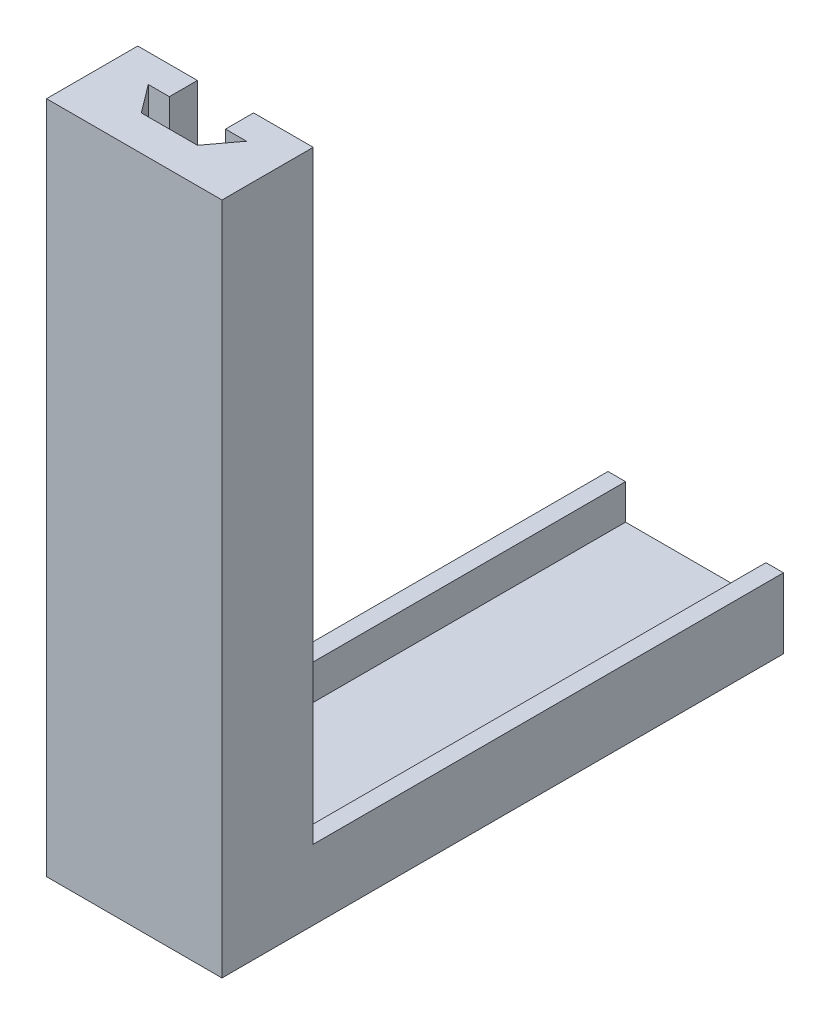
SolidWorks part; units mm, degrees
ref_plane "Front Plane" through (0, 0, 0) normal (0, 0, 1) x (1, 0, 0)
ref_plane "Top Plane" through (0, 0, 0) normal (0, 1, 0) x (1, 0, 0)
ref_plane "Right Plane" through (0, 0, 0) normal (1, 0, 0) x (0, 0, -1)
sketch "Sketch1" plane through (0, 0, 0) normal (0, 1, 0) x (1, 0, 0)
  line L1 (-12.5, -40) -> (12.5, -40)
  line L2 (-12.5, -40) -> (-12.5, 40)
  line L3 (-12.5, 40) -> (12.5, 40)
  line L4 (12.5, -40) -> (12.5, 40)
  line L5 (-12.5, -40) -> (12.5, 40) construction
  line L6 (-12.5, 40) -> (12.5, -40) construction
  point P0 (0, 0)
  dimension "D1" = 80
  dimension "D2" = 25
extrude "Boss-Extrude1" add sketch "Sketch1" along normal blind 10
sketch "Sketch2" plane through (0, 10, 0) normal (0, 1, 0) x (1, 0, 0)
  line L0 (12.5, -40) -> (12.5, 40) construction
  line L1 (-12.5, -40) -> (12.5, -40)
  line L2 (-12.5, -40) -> (-12.5, -27)
  line L3 (-12.5, -27) -> (12.5, -27)
  line L4 (12.5, -40) -> (12.5, -27)
  dimension "D1" = 13
extrude "Boss-Extrude2" add sketch "Sketch2" along normal blind 86 contours L3 L4 L1 L2
sketch "Sketch3" plane through (0, 96, 0) normal (0, 1, 0) x (1, 0, 0)
  line L0 (0, -27) -> (0, -40) construction
  line L1 (-12.5, -27) -> (12.5, -27) construction
  line L2 (-12.5, -40) -> (12.5, -40) construction
  line L3 (-4, -27) -> (4, -27)
  line L5 (-12.5, -27) -> (12.5, -27) construction
  line L6 (-4, -27) -> (-4, -31)
  line L7 (-4, -31) -> (-7, -31)
  line L8 (-7, -31) -> (-4, -35)
  line L9 (-4, -35) -> (4, -35)
  line L10 (4, -35) -> (7, -31)
  line L11 (7, -31) -> (4, -31)
  line L12 (4, -31) -> (4, -27)
  point P10 (0, 0)
  point P17 (0, 0)
  point P18 (0, 0)
  dimension "D1" = 8
  dimension "D2" = 4
  dimension "D3" = 4
  dimension "D4" = 3
extrude "Cut-Extrude1" cut sketch "Sketch3" against normal blind 91
sketch "Sketch4" plane through (0, 10, 0) normal (0, 1, 0) x (1, 0, 0)
  line L0 (0, 40) -> (0, -27) construction
  line L1 (12.5, 40) -> (-12.5, 40) construction
  line L2 (-4, -27) -> (4, -27) construction
  line L3 (4, -27) -> (12.5, -27) construction
  line L4 (-10, 40) -> (10, 40)
  line L5 (-10, 40) -> (-10, -27)
  line L6 (-10, -27) -> (10, -27)
  line L7 (10, 40) -> (10, -27)
  line L8 (4, -27) -> (12.5, -27) construction
  dimension "D1" = 20
extrude "Cut-Extrude2" cut sketch "Sketch4" against normal blind 5
